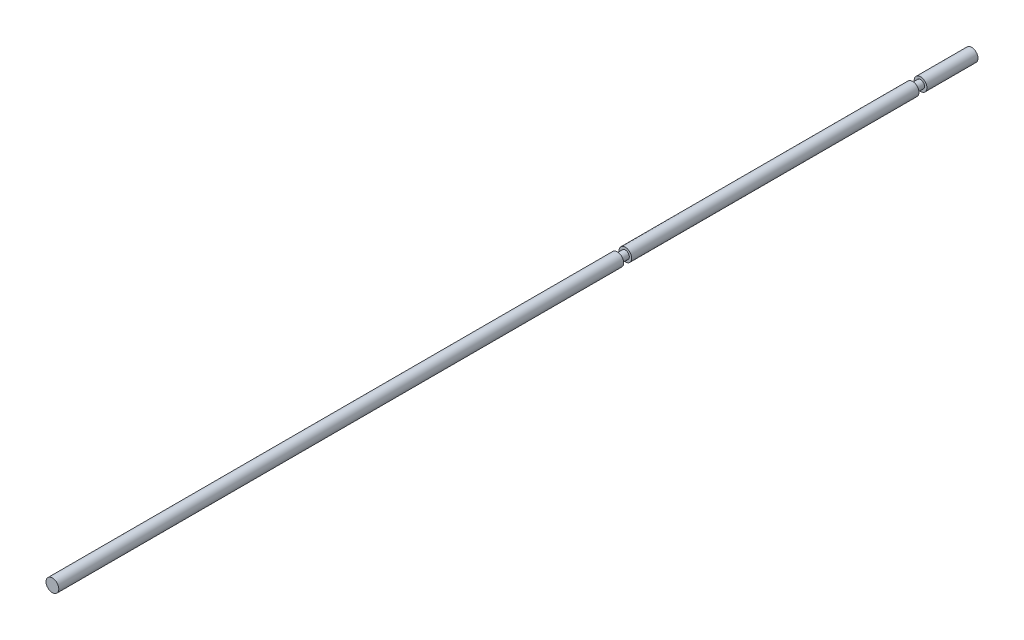
SolidWorks part; units mm, degrees
ref_plane "Front Plane" through (0, 0, 0) normal (0, 0, 1) x (1, 0, 0)
ref_plane "Top Plane" through (0, 0, 0) normal (0, 1, 0) x (1, 0, 0)
ref_plane "Right Plane" through (0, 0, 0) normal (1, 0, 0) x (0, 0, -1)
sketch "Sketch1" plane through (0, 0, 0) normal (0, 0, 1) x (1, 0, 0)
  circle A0 centre (0, 0) radius 6.35
  dimension "D1" = 12.7
extrude "Boss-Extrude1" add sketch "Sketch1" along normal blind 914.4
ref_plane "Plane1" through (0, 0, 50.8) normal (0, 0, -1) x (-1, 0, 0)
sketch "Sketch3" plane through (0, 0, 50.8) normal (0, 0, -1) x (-1, 0, 0)
  circle A0 centre (0, 0) radius 3.9688
  circle A1 centre (0, 0) radius 6.35
  dimension "D1" = 7.9375
  dimension "D2" = 12.7
extrude "Cut-Extrude1" cut sketch "Sketch3" against normal blind 7.9375 contours A1 A0
ref_plane "Plane2" through (0, 0, 344.4875) normal (0, 0, -1) x (-1, 0, 0)
sketch "Sketch4" plane through (0, 0, 344.4875) normal (0, 0, -1) x (-1, 0, 0)
  circle A0 centre (0, 0) radius 3.9688
  circle A1 centre (0, 0) radius 6.35
  dimension "D1" = 12.7
  dimension "D2" = 7.9375
extrude "Cut-Extrude2" cut sketch "Sketch4" against normal blind 7.9375
